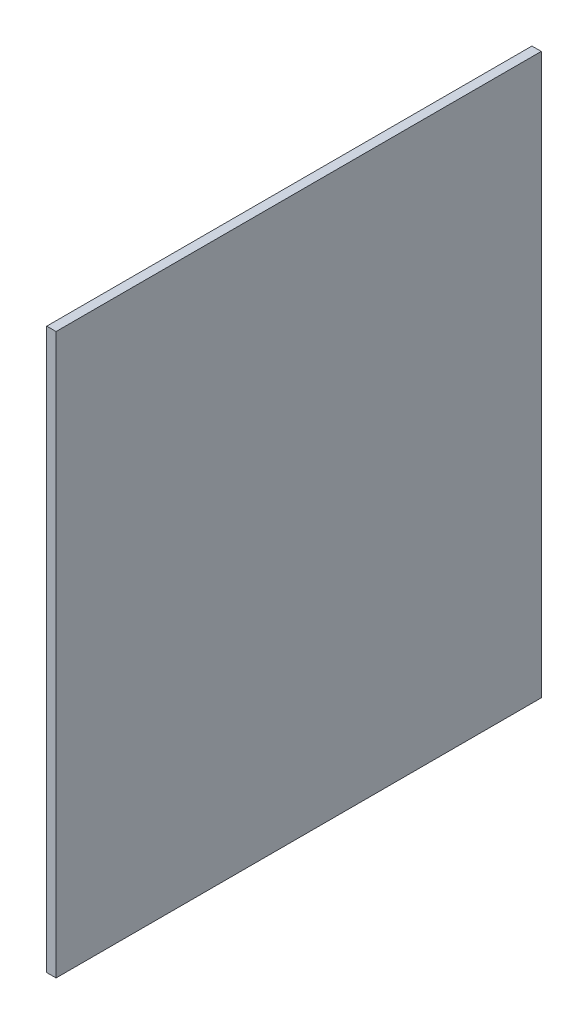
SolidWorks part; units mm, degrees
material "AISI 1020 Steel, Cold Rolled"
ref_plane "Front Plane" through (0, 0, 0) normal (0, 0, 1) x (1, 0, 0)
ref_plane "Top Plane" through (0, 0, 0) normal (0, 1, 0) x (1, 0, 0)
ref_plane "Right Plane" through (0, 0, 0) normal (1, 0, 0) x (0, 0, -1)
sketch "Sketch1" plane through (0, 0, 0) normal (0, 0, 1) x (1, 0, 0)
  line L0 (0, 0) -> (0, 300)
  line L1 (0, 300) -> (5, 300)
  line L2 (5, 300) -> (5, 0)
  line L3 (5, 0) -> (0, 0)
extrude "Boss-Extrude1" add sketch "Sketch1" along normal blind 260
